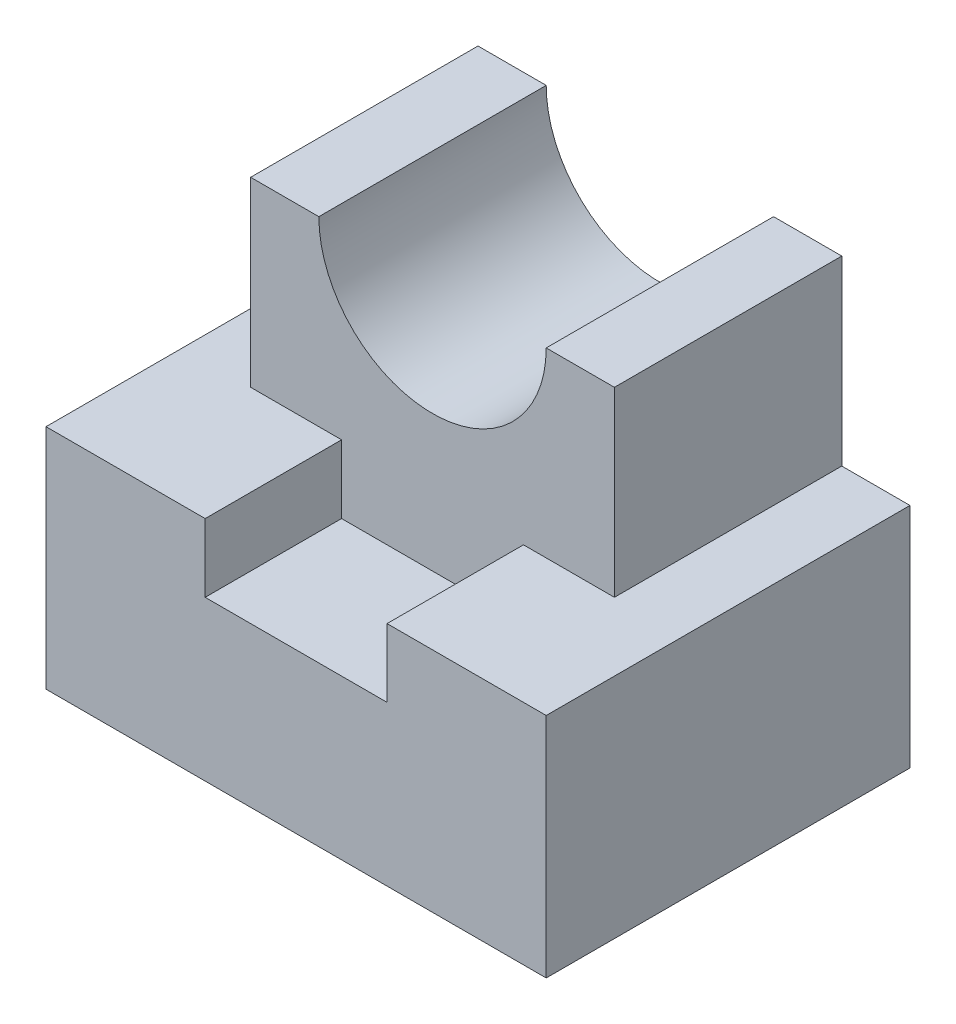
SolidWorks part; units mm, degrees
ref_plane "Front Plane" through (0, 0, 0) normal (0, 0, 1) x (1, 0, 0)
ref_plane "Top Plane" through (0, 0, 0) normal (0, 1, 0) x (1, 0, 0)
ref_plane "Right Plane" through (0, 0, 0) normal (1, 0, 0) x (0, 0, -1)
sketch "Sketch3" plane through (0, 0, 0) normal (0, 1, 0) x (1, 0, 0)
  line L0 (0, 40) -> (0, -40) construction
  line L1 (-55, 40) -> (55, 40)
  line L2 (-55, 40) -> (-55, -40)
  line L3 (-55, -40) -> (55, -40)
  line L4 (55, 40) -> (55, -40)
  point P6 (0, 0)
  dimension "D1" = 80
  dimension "D2" = 110
extrude "Boss-Extrude2" add sketch "Sketch3" along normal blind 50
sketch "Sketch6" plane through (0, 0, 0) normal (0, -1, 0) x (1, 0, 0)
  line L0 (0, -40) -> (0, 40) construction
  line L1 (-40, -40) -> (40, -40)
  line L2 (-40, -40) -> (-40, 10)
  line L3 (-40, 10) -> (40, 10)
  line L4 (40, -40) -> (40, 10)
  line L5 (55, -40) -> (-55, -40) construction
  line L6 (-55, 40) -> (55, 40) construction
  point P4 (0, 0)
  point P9 (0, 0)
  point P10 (0, 0)
  point P11 (0, 0)
  dimension "D1" = 50
  dimension "D2" = 80
extrude "Boss-Extrude3" add sketch "Sketch6" against normal blind 90
sketch "Sketch7" plane through (0, 0, -40) normal (0, 0, -1) x (-1, 0, 0)
  line L0 (40, 90) -> (-40, 90) construction
  circle A0 centre (0, 90) radius 25
  dimension "D1" = 50
extrude "Cut-Extrude1" cut sketch "Sketch7" against normal through all
sketch "Sketch8" plane through (0, 0, 40) normal (0, 0, 1) x (1, 0, 0)
  line L1 (-40, 50) -> (40, 50) construction
  line L2 (-20, 50) -> (20, 50)
  line L3 (-20, 50) -> (-20, 35)
  line L4 (-20, 35) -> (20, 35)
  line L5 (20, 50) -> (20, 35)
  line L6 (0, 50) -> (0, 0) construction
  line L7 (-55, 0) -> (55, 0) construction
  dimension "D1" = 15
  dimension "D2" = 40
extrude "Cut-Extrude2" cut sketch "Sketch8" against normal up to surface (30 mm away) and the other way through all up to face at (0, 72.5, 10)
